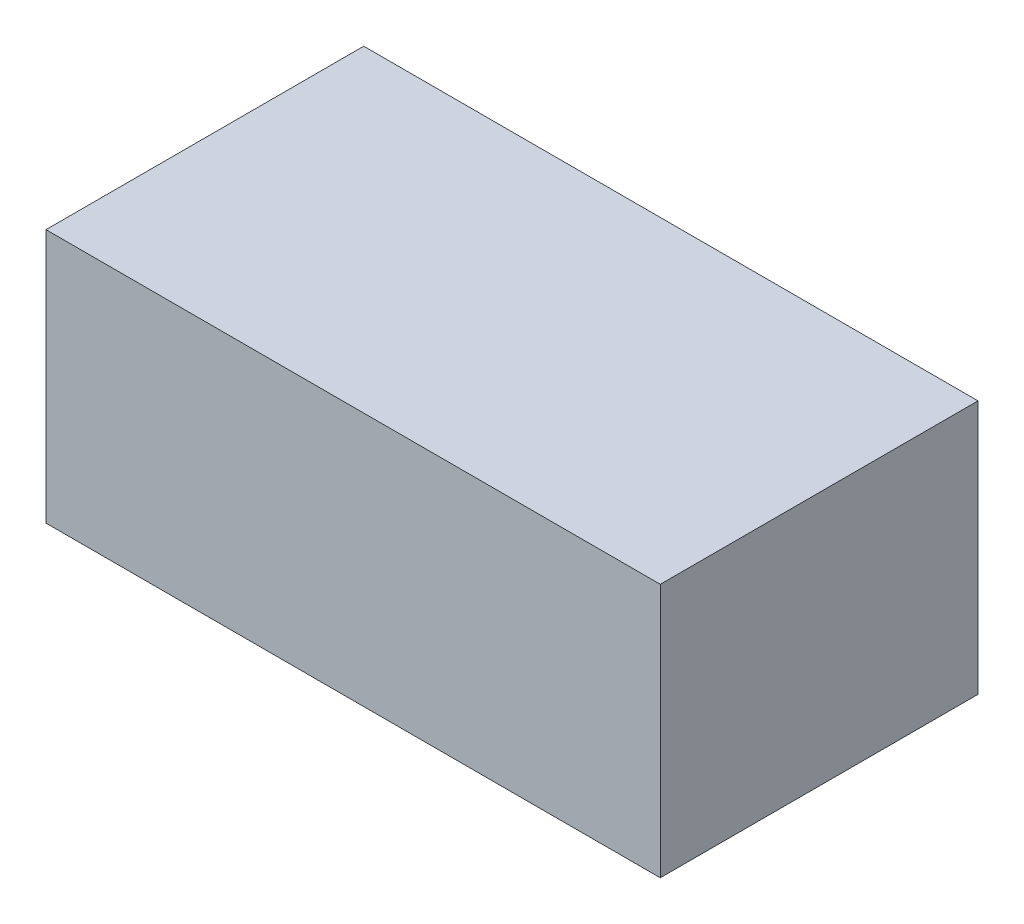
SolidWorks part; units mm, degrees
ref_plane "前视基准面" through (0, 0, 0) normal (0, 0, 1) x (1, 0, 0)
ref_plane "上视基准面" through (0, 0, 0) normal (0, 1, 0) x (1, 0, 0)
ref_plane "右视基准面" through (0, 0, 0) normal (1, 0, 0) x (0, 0, -1)
sketch "草图1" plane through (0, 0, 0) normal (0, 1, 0) x (1, 0, 0)
  line L1 (-29, -15) -> (29, -15)
  line L2 (-29, -15) -> (-29, 15)
  line L3 (-29, 15) -> (29, 15)
  line L4 (29, -15) -> (29, 15)
  line L5 (-29, -15) -> (29, 15) construction
  line L6 (-29, 15) -> (29, -15) construction
  point P0 (0, 0)
  dimension "D1" = 58
  dimension "D2" = 30
extrude "凸台-拉伸1" add sketch "草图1" along normal blind 24
